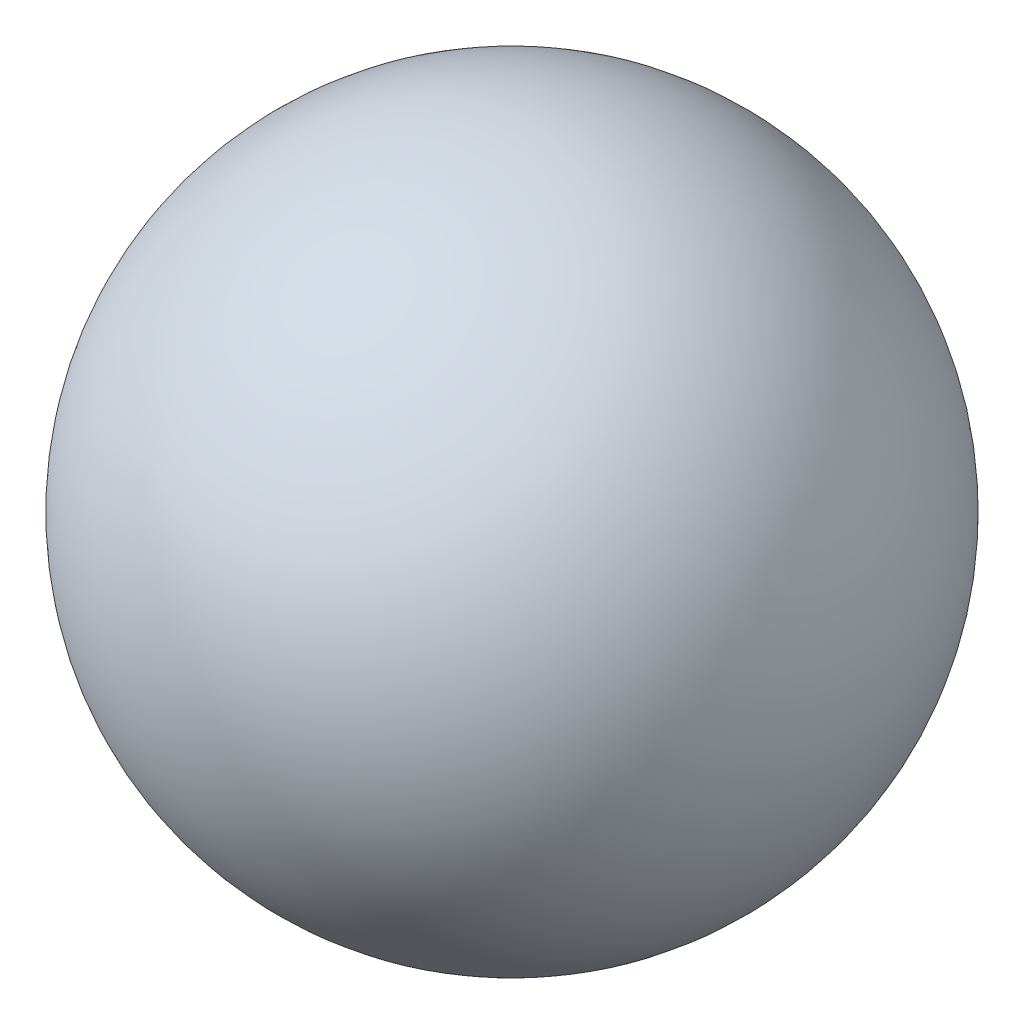
SolidWorks part; units mm, degrees
ref_plane "Front Plane" through (0, 0, 0) normal (0, 0, 1) x (1, 0, 0)
ref_plane "Top Plane" through (0, 0, 0) normal (0, 1, 0) x (1, 0, 0)
ref_plane "Right Plane" through (0, 0, 0) normal (1, 0, 0) x (0, 0, -1)
sketch "Sketch1" plane through (0, 0, 0) normal (0, 0, 1) x (1, 0, 0)
  line L0 (0, -4) -> (0, 4)
  arc A0 (0, 4) -> (0, -4) centre (0, 0) cw
revolve "Revolve1" add sketch "Sketch1" angle 360 about L0
